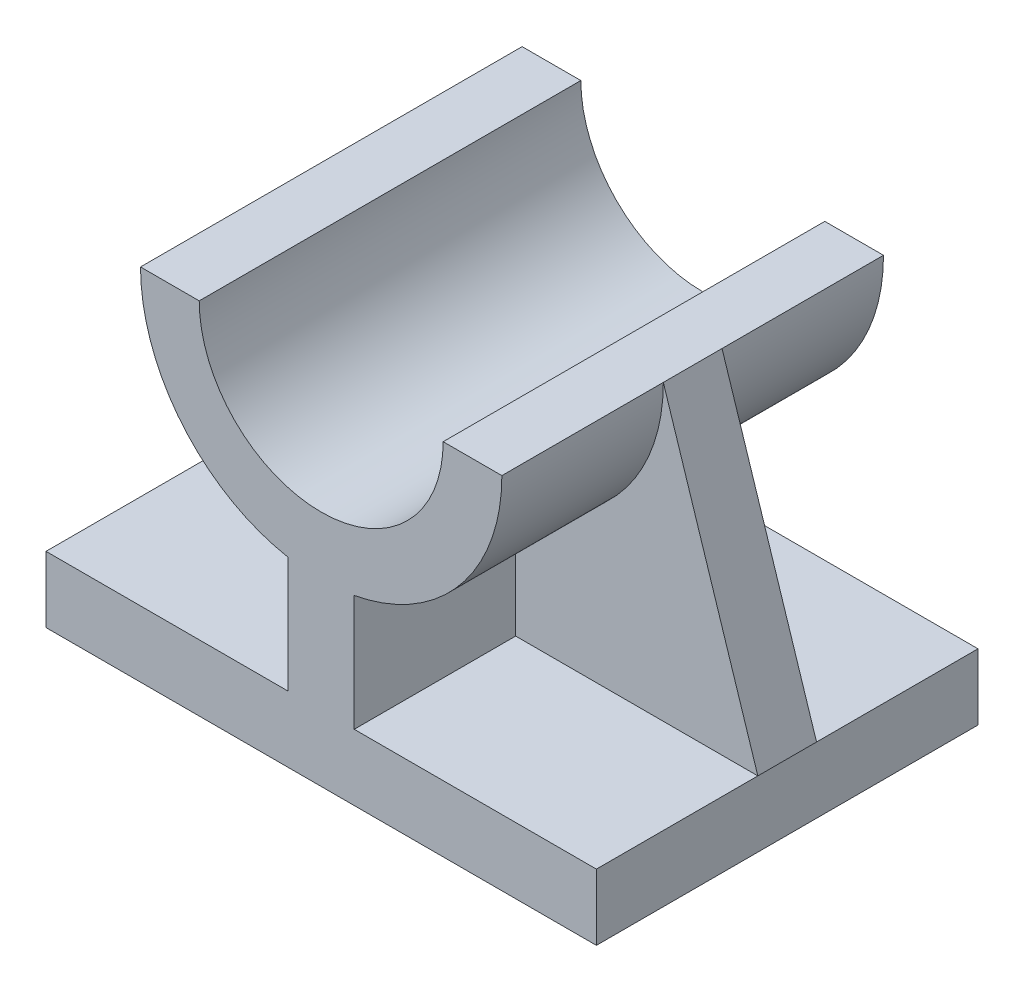
SolidWorks part; units mm, degrees
ref_plane "Front Plane" through (0, 0, 0) normal (0, 0, 1) x (1, 0, 0)
ref_plane "Top Plane" through (0, 0, 0) normal (0, 1, 0) x (1, 0, 0)
ref_plane "Right Plane" through (0, 0, 0) normal (1, 0, 0) x (0, 0, -1)
sketch "Sketch1" plane through (0, 0, 0) normal (0, 0, 1) x (1, 0, 0)
  line L0 (-37.9139, 0) -> (37.0861, 0)
  line L1 (37.0861, 0) -> (37.0861, 9)
  line L2 (37.0861, 9) -> (4.0861, 9)
  line L3 (-37.9139, 0) -> (-37.9139, 9)
  line L4 (-37.9139, 9) -> (-4.9139, 9)
  line L5 (-4.9139, 9) -> (-4.9139, 24.7935)
  line L6 (4.0861, 9) -> (4.0861, 24.7935)
  line L7 (-4.9139, 9) -> (4.0861, 9)
  line L8 (-0.4139, 9) -> (-0.4139, 28.2543) construction
  line L9 (-25.0352, 49) -> (24.2073, 49)
  line L10 (-25.0352, 49) -> (-17.0352, 49)
  circle A0 centre (-0.4139, 49) radius 24.6213
  circle A1 centre (-0.4139, 49) radius 16.6213
  dimension "D1" = 75
  dimension "D2" = 9
  dimension "D3" = 33
  dimension "D4" = 33
  dimension "D5" = 9
  dimension "D6" = 40
  dimension "D7" = 8
extrude "Boss-Extrude1" add sketch "Sketch1" against normal blind 52
move or copy body "Body-Move/Copy1" bodies to move or copy 101 copy no translate (0, 0, 26) parameters "D1"=0, "D2"=0, "D3"=26
sketch "Sketch3" plane through (0, 0, 0) normal (0, 0, 1) x (1, 0, 0)
  line L0 (24.2073, 49) -> (37.0861, 9)
  line L1 (-25.0352, 49) -> (-37.9139, 9)
  line L2 (-4.9139, 9) -> (-37.9139, 9)
  line L3 (37.0861, 9) -> (4.0861, 9)
  line L4 (-4.9139, 24.7935) -> (-4.9139, 9)
  line L5 (4.0861, 9) -> (4.0861, 24.7935)
  arc A0 (-25.0352, 49) -> (-4.9139, 24.7935) centre (-0.4139, 49) ccw
  arc A1 (4.0861, 24.7935) -> (24.2073, 49) centre (-0.4139, 49) ccw
extrude "Boss-Extrude2" add sketch "Sketch3" along normal mid plane 8
